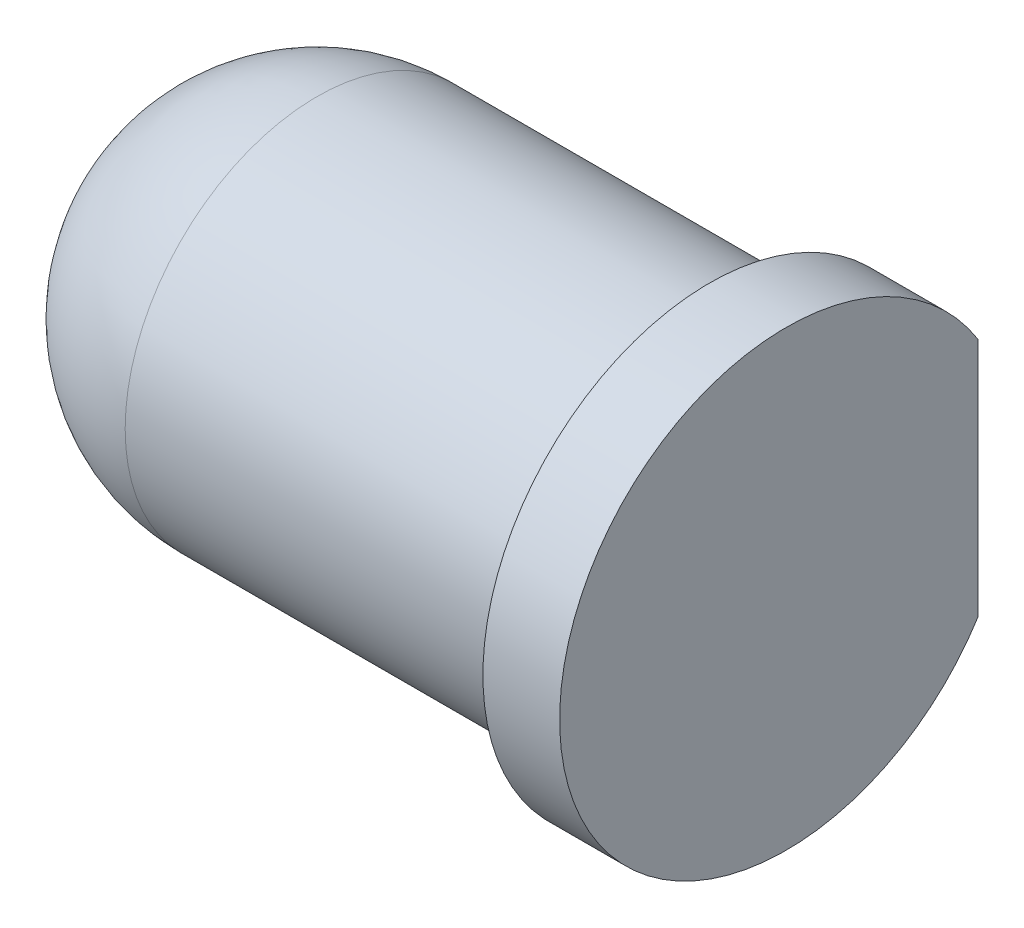
SolidWorks part; units mm, degrees
material "Custom Plastic"
ref_plane "Front Plane" through (0, 0, 0) normal (0, 0, 1) x (1, 0, 0)
ref_plane "Top Plane" through (0, 0, 0) normal (0, 1, 0) x (1, 0, 0)
ref_plane "Right Plane" through (0, 0, 0) normal (1, 0, 0) x (0, 0, -1)
sketch "Sketch2" plane through (0, 0, 0) normal (1, 0, 0) x (0, 0, -1)
  circle A0 centre (0, 0) radius 2.5
extrude "Boss-Extrude1" add sketch "Sketch2" along normal mid plane 7.6
sketch "Sketch3" plane through (3.8, 0, 0) normal (1, 0, 0) x (0, 0, -1)
  circle A0 centre (0, 0) radius 2.95
extrude "Boss-Extrude3" add sketch "Sketch3" along normal blind 1
sketch "Sketch4" plane through (3.8, 0, 0) normal (-1, 0, 0) x (0, 0, 1)
  line L1 (-2.5, -4.0382) -> (-3.3658, -4.0382)
  line L2 (-2.5, 0) -> (-2.5, 5) construction
  line L3 (-2.5, -4.0382) -> (-2.5, 2.9011)
  line L4 (-2.5, 2.9011) -> (-3.3658, 2.9011)
  line L5 (-3.3658, -4.0382) -> (-3.3658, 2.9011)
  circle A0 centre (0, 0) radius 2.5 construction
extrude "Cut-Extrude1" cut sketch "Sketch4" against normal blind 1
sketch "Sketch5" plane through (0, 0, 0) normal (0, 1, 0) x (1, 0, 0)
  line L0 (-3.8, 2.5) -> (-3.8, -2.5) construction
  line L1 (-3.8, -0.01) -> (-3.8, -2.5)
  line L2 (-3.8, -2.5) -> (-1.31, -2.5)
  line L3 (-4.3173, 0) -> (5.404, 0) construction
  arc A0 (-3.8, -0.01) -> (-1.31, -2.5) centre (-1.31, -0.01) ccw
revolve "Cut-Revolve4" cut sketch "Sketch5" angle 360 about L3
